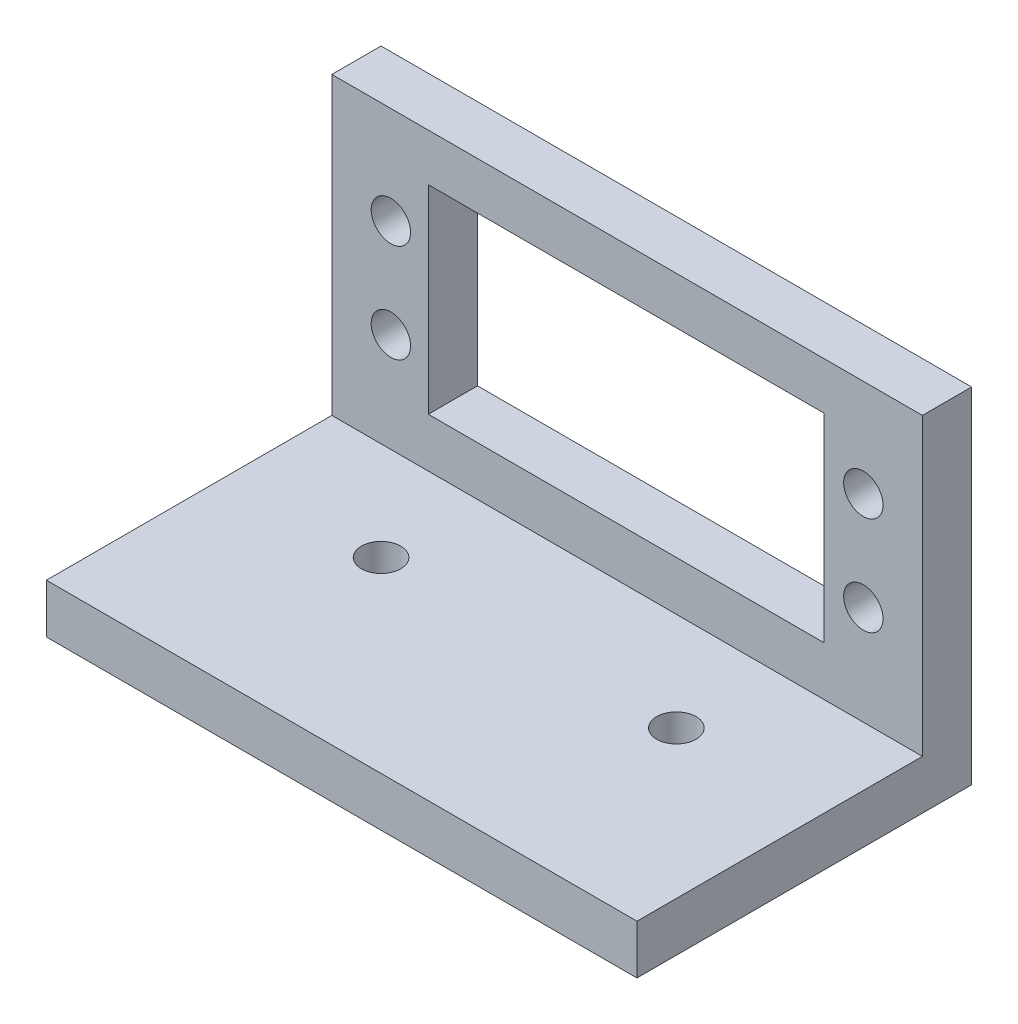
SolidWorks part; units mm, degrees
ref_plane "Front Plane" through (0, 0, 0) normal (0, 0, 1) x (1, 0, 0)
ref_plane "Top Plane" through (0, 0, 0) normal (0, 1, 0) x (1, 0, 0)
ref_plane "Right Plane" through (0, 0, 0) normal (1, 0, 0) x (0, 0, -1)
sketch "Sketch1" plane through (0, 0, 0) normal (0, 0, 1) x (1, 0, 0)
  line L0 (17.9, -8.8986) -> (17.9, 10.1014) construction
  line L1 (-32.1, 15.5014) -> (27.9, 15.5014)
  line L2 (-32.1, 15.5014) -> (-32.1, -19.4986)
  line L3 (-32.1, -19.4986) -> (27.9, -19.4986)
  line L4 (27.9, 15.5014) -> (27.9, -19.4986)
  line L5 (-32.1, 15.5014) -> (27.9, -19.4986) construction
  line L6 (-32.1, -19.4986) -> (27.9, 15.5014) construction
  line L7 (-22.3, 10.7014) -> (17.9, 10.7014)
  line L8 (-22.3, 10.7014) -> (-22.3, -9.4986)
  line L9 (-22.3, -9.4986) -> (17.9, -9.4986)
  line L10 (17.9, 10.7014) -> (17.9, -9.4986)
  line L11 (-22.3, 10.7014) -> (17.9, -9.4986) construction
  line L12 (-22.3, -9.4986) -> (17.9, 10.7014) construction
  point P0 (0, 0)
  point P6 (-2.2, 0.6014)
  dimension "D2" = 10
  dimension "D3" = 10
  dimension "D4" = 35
  dimension "D5" = 60
  dimension "D6" = 40.2
  dimension "D7" = 20.2
extrude "Boss-Extrude1" add sketch "Sketch1" along normal blind 5
sketch "Sketch2" plane through (0, 0, 5) normal (0, 0, 1) x (1, 0, 0)
  line L0 (27.9, -19.4986) -> (27.9, 15.5014) construction
  line L1 (-32.1, -19.4986) -> (27.9, -19.4986)
  line L2 (-32.1, -19.4986) -> (-32.1, -14.4986)
  line L3 (-32.1, -14.4986) -> (27.9, -14.4986)
  line L4 (27.9, -19.4986) -> (27.9, -14.4986)
  dimension "D1" = 5
extrude "Boss-Extrude2" add sketch "Sketch2" along normal up to surface (29 mm away)
sketch "Sketch3" plane through (0, -19.4986, 0) normal (0, -1, 0) x (-1, 0, 0)
  circle A0 centre (17.1, -15) radius 2
  circle A1 centre (-12.9, -15) radius 2
  circle A2 centre (17.1, -15) radius 2 construction
extrude "Cut-Extrude1" cut sketch "Sketch3" against normal up to surface (10 mm away) up to face at (-2.2, -9.4986, 2.5)
sketch "Sketch4" plane through (0, 0, 5) normal (0, 0, 1) x (1, 0, 0)
  circle A0 centre (21.9, 5.6014) radius 2
  circle A1 centre (21.9, -4.3986) radius 2
  circle A2 centre (-26.1, -4.3986) radius 2
  circle A3 centre (-26.1, 5.6014) radius 2
  point P12 (0, 0)
  point P13 (0, 0)
  point P14 (0, 0)
  point P15 (0, 0)
extrude "Cut-Extrude2" cut sketch "Sketch4" against normal through all
